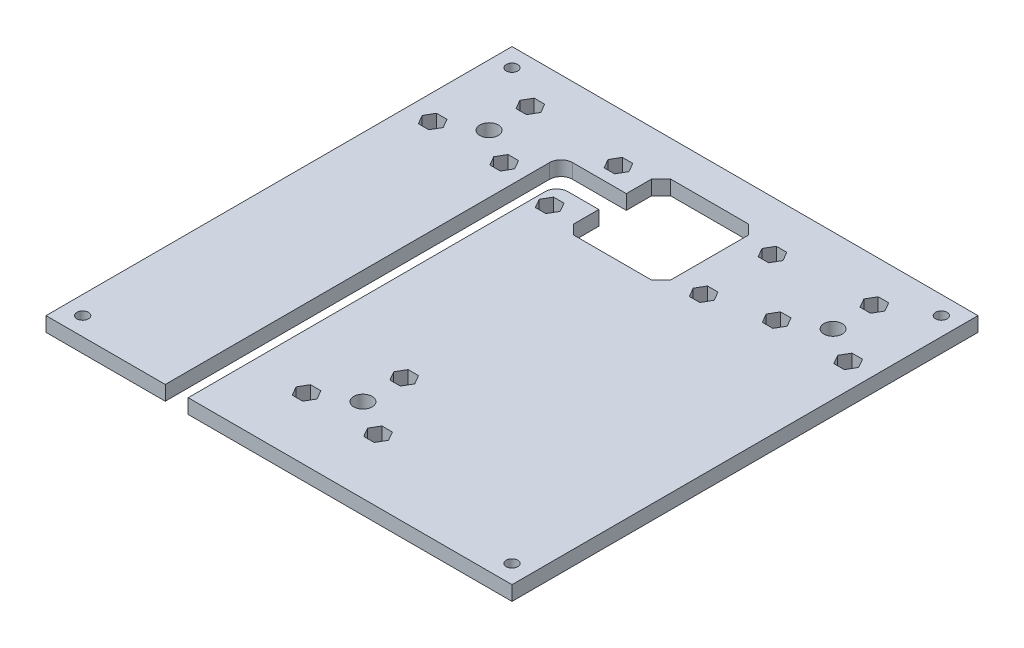
SolidWorks part; units mm, degrees
ref_plane "Plan de face" through (0, 0, 0) normal (0, 0, 1) x (1, 0, 0)
ref_plane "Plan de dessus" through (0, 0, 0) normal (0, 1, 0) x (1, 0, 0)
ref_plane "Plan de droite" through (0, 0, 0) normal (1, 0, 0) x (0, 0, -1)
sketch "Esquisse1" plane through (0, 0, 0) normal (0, 1, 0) x (1, 0, 0)
  line L1 (-101.6, -101.6) -> (101.6, -101.6)
  line L2 (-101.6, -101.6) -> (-101.6, 101.6)
  line L3 (-101.6, 101.6) -> (101.6, 101.6)
  line L4 (101.6, -101.6) -> (101.6, 101.6)
  line L5 (-101.6, -101.6) -> (101.6, 101.6) construction
  line L6 (-101.6, 101.6) -> (101.6, -101.6) construction
  point P0 (0, 0)
  dimension "D1" = 203.2
extrude "Boss.-Extru.1" add sketch "Esquisse1" along normal blind 6.35
sketch "Esquisse2" plane through (0, 6.35, 0) normal (0, 1, 0) x (1, 0, 0)
  circle A0 centre (-75, 65) radius 4
  circle A1 centre (75, 65) radius 4
  circle A2 centre (0, -65) radius 4
  dimension "D1" = 8
  dimension "D2" = 65
  dimension "D3" = 65
  dimension "D4" = 150
  dimension "D5" = 75
extrude "Enlèv. mat.-Extru.1" cut sketch "Esquisse2" against normal through all
sketch "Esquisse3" plane through (0, 6.35, 0) normal (0, 1, 0) x (1, 0, 0)
  line L0 (-17.05, 86.15) -> (-21.15, 82.05)
  line L1 (-21.15, 82.05) -> (-21.15, 47.95)
  line L2 (-21.15, 47.95) -> (-17.05, 43.85)
  line L3 (-17.05, 43.85) -> (17.05, 43.85)
  line L4 (17.05, 43.85) -> (21.15, 47.95)
  line L5 (21.15, 47.95) -> (21.15, 82.05)
  line L6 (21.15, 82.05) -> (17.05, 86.15)
  line L7 (17.05, 86.15) -> (-17.05, 86.15)
  line L9 (-75, 65) -> (75, 65) construction
  point P8 (0, 43.85)
  point P11 (0, 86.15)
  point P12 (-21.15, 65)
  point P13 (21.15, 65)
  dimension "D2" = 42.3
  dimension "D3" = 34.1
extrude "Enlèv. mat.-Extru.2" cut sketch "Esquisse3" against normal through all
sketch "Esquisse4" plane through (0, 6.35, 0) normal (0, 1, 0) x (1, 0, 0)
  line L0 (-101.6, -101.6) -> (101.6, -101.6) construction
  line L1 (-49.6, -101.6) -> (-39.6, -101.6)
  line L2 (-49.6, -101.6) -> (-49.6, 71)
  line L4 (-39.6, -101.6) -> (-39.6, 59)
  line L5 (-21.15, 82.05) -> (-21.15, 47.95) construction
  line L6 (-49.6, 71) -> (-21.15, 71)
  line L8 (-39.6, 59) -> (-21.15, 59)
  line L9 (-21.15, 71) -> (-21.15, 59)
  line L10 (-101.6, 101.6) -> (-101.6, -101.6) construction
  dimension "D1" = 10
  dimension "D2" = 52
  dimension "D3" = 12
  dimension "D4" = 11.05
extrude "Enlèv. mat.-Extru.3" cut sketch "Esquisse4" against normal through all
fillet "Congé1" radius 5 2 edges at (-49.6, 3.175, -71) (-39.6, 3.175, -59)
sketch "Esquisse5" plane through (0, 6.35, 0) normal (0, 1, 0) x (1, 0, 0)
  line L0 (-28.8524, 49.85) -> (-31.1387, 45.89)
  line L1 (-33.425, 49.85) -> (-33.425, 54.8456) construction
  line L2 (-31.1387, 45.89) -> (-35.7113, 45.89)
  line L3 (-35.7113, 45.89) -> (-37.9976, 49.85)
  line L4 (-37.9976, 49.85) -> (-35.7113, 53.81)
  line L5 (-35.7113, 53.81) -> (-31.1387, 53.81)
  line L6 (-31.1387, 53.81) -> (-28.8524, 49.85)
  line L7 (-33.425, 49.85) -> (-37.4356, 49.85) construction
  point P2 (-33.425, 53.81)
  dimension "D1" = 7.92
  dimension "D2" = 7.92
  dimension "D3" = 7.92
extrude "Enlèv. mat.-Extru.5" cut sketch "Esquisse5" against normal through all
sketch "Esquisse7" plane through (0, 6.35, 0) normal (0, 1, 0) x (1, 0, 0)
  line L0 (-31.1387, 75.89) -> (-35.7113, 75.89)
  line L1 (-35.7113, 75.89) -> (-37.9976, 79.85)
  line L2 (-37.9976, 79.85) -> (-35.7113, 83.81)
  line L3 (-35.7113, 83.81) -> (-31.1387, 83.81)
  line L4 (-31.1387, 83.81) -> (-28.8524, 79.85)
  line L6 (-28.8524, 79.85) -> (-31.1387, 75.89)
  line L8 (-33.425, 79.85) -> (-37.5841, 79.85) construction
  line L9 (-33.425, 79.85) -> (-33.425, 74.6708) construction
  point P8 (-33.425, 75.89)
  dimension "D1" = 7.92
  dimension "D2" = 7.92
  dimension "D3" = 7.92
extrude "Enlèv. mat.-Extru.6" cut sketch "Esquisse7" against normal through all
sketch "Esquisse8" plane through (0, 6.35, 0) normal (0, 1, 0) x (1, 0, 0)
  line L0 (36.0113, 45.89) -> (31.4387, 45.89)
  line L1 (31.4387, 45.89) -> (29.1524, 49.85)
  line L2 (29.1524, 49.85) -> (31.4387, 53.81)
  line L3 (31.4387, 53.81) -> (36.0113, 53.81)
  line L4 (36.0113, 53.81) -> (38.2976, 49.85)
  line L5 (38.2976, 49.85) -> (36.0113, 45.89)
  line L6 (33.725, 49.85) -> (36.8565, 49.85) construction
  line L7 (33.725, 49.85) -> (33.725, 61.6399) construction
  point P9 (33.725, 45.89)
  dimension "D1" = 7.92
  dimension "D2" = 7.92
  dimension "D3" = 7.92
extrude "Enlèv. mat.-Extru.7" cut sketch "Esquisse8" against normal through all
sketch "Esquisse9" plane through (0, 6.35, 0) normal (0, 1, 0) x (1, 0, 0)
  line L0 (36.0113, 75.89) -> (31.4387, 75.89)
  line L1 (31.4387, 75.89) -> (29.1524, 79.85)
  line L2 (29.1524, 79.85) -> (31.4387, 83.81)
  line L3 (31.4387, 83.81) -> (36.0113, 83.81)
  line L4 (36.0113, 83.81) -> (38.2976, 79.85)
  line L5 (38.2976, 79.85) -> (36.0113, 75.89)
  line L6 (33.725, 79.85) -> (33.725, 71.0093) construction
  line L7 (33.725, 71.0093) -> (33.725, 79.85) construction
  line L8 (33.725, 79.85) -> (36.6273, 79.85) construction
  point P11 (33.725, 83.81)
  dimension "D1" = 7.92
  dimension "D2" = 7.92
  dimension "D3" = 7.92
extrude "Enlèv. mat.-Extru.8" cut sketch "Esquisse9" against normal through all
sketch "Esquisse10" plane through (0, 6.35, 0) normal (0, 1, 0) x (1, 0, 0)
  line L0 (101.6, 101.6) -> (-101.6, 101.6) construction
  line L1 (20.1611, -74) -> (17.8748, -70.04)
  line L2 (17.8748, -70.04) -> (13.3022, -70.04)
  line L3 (13.3022, -70.04) -> (11.0158, -74)
  line L4 (11.0158, -74) -> (13.3022, -77.96)
  line L5 (13.3022, -77.96) -> (17.8748, -77.96)
  line L6 (17.8748, -77.96) -> (20.1611, -74)
  line L7 (-20.1611, -74) -> (-17.8748, -77.96)
  line L8 (-17.8748, -77.96) -> (-13.3022, -77.96)
  line L9 (-13.3022, -77.96) -> (-11.0158, -74)
  line L10 (-11.0158, -74) -> (-13.3022, -70.04)
  line L11 (-13.3022, -70.04) -> (-17.8748, -70.04)
  line L12 (-17.8748, -70.04) -> (-20.1611, -74)
  line L13 (-4.5726, -47) -> (-2.2863, -50.96)
  line L14 (-2.2863, -50.96) -> (2.2863, -50.96)
  line L15 (2.2863, -50.96) -> (4.5726, -47)
  line L16 (4.5726, -47) -> (2.2863, -43.04)
  line L17 (2.2863, -43.04) -> (-2.2863, -43.04)
  line L18 (-2.2863, -43.04) -> (-4.5726, -47)
  line L19 (-63.9842, 56) -> (-61.6978, 52.04)
  line L20 (-61.6978, 52.04) -> (-57.1252, 52.04)
  line L21 (-57.1252, 52.04) -> (-54.8389, 56)
  line L22 (-54.8389, 56) -> (-57.1252, 59.96)
  line L23 (-57.1252, 59.96) -> (-61.6978, 59.96)
  line L24 (-61.6978, 59.96) -> (-63.9842, 56)
  line L25 (-95.1611, 56) -> (-92.8748, 52.04)
  line L26 (-92.8748, 52.04) -> (-88.3022, 52.04)
  line L27 (-88.3022, 52.04) -> (-86.0158, 56)
  line L28 (-86.0158, 56) -> (-88.3022, 59.96)
  line L29 (-88.3022, 59.96) -> (-92.8748, 59.96)
  line L30 (-92.8748, 59.96) -> (-95.1611, 56)
  line L31 (-79.5726, 83) -> (-77.2863, 79.04)
  line L32 (-77.2863, 79.04) -> (-72.7137, 79.04)
  line L33 (-72.7137, 79.04) -> (-70.4274, 83)
  line L34 (-70.4274, 83) -> (-72.7137, 86.96)
  line L35 (-72.7137, 86.96) -> (-77.2863, 86.96)
  line L36 (-77.2863, 86.96) -> (-79.5726, 83)
  line L37 (54.8389, 56) -> (57.1252, 52.04)
  line L38 (57.1252, 52.04) -> (61.6978, 52.04)
  line L39 (61.6978, 52.04) -> (63.9842, 56)
  line L40 (63.9842, 56) -> (61.6978, 59.96)
  line L41 (61.6978, 59.96) -> (57.1252, 59.96)
  line L42 (57.1252, 59.96) -> (54.8389, 56)
  line L43 (95.1611, 56) -> (92.8748, 59.96)
  line L44 (92.8748, 59.96) -> (88.3022, 59.96)
  line L45 (88.3022, 59.96) -> (86.0158, 56)
  line L46 (86.0158, 56) -> (88.3022, 52.04)
  line L47 (88.3022, 52.04) -> (92.8748, 52.04)
  line L48 (92.8748, 52.04) -> (95.1611, 56)
  line L49 (70.4274, 83) -> (72.7137, 79.04)
  line L50 (72.7137, 79.04) -> (77.2863, 79.04)
  line L51 (77.2863, 79.04) -> (79.5726, 83)
  line L52 (79.5726, 83) -> (77.2863, 86.96)
  line L53 (77.2863, 86.96) -> (72.7137, 86.96)
  line L54 (72.7137, 86.96) -> (70.4274, 83)
  circle A0 centre (15.5885, -74) radius 3.96 construction
  circle A1 centre (-15.5885, -74) radius 3.96 construction
  circle A2 centre (0, -47) radius 3.96 construction
  circle A3 centre (-59.4115, 56) radius 3.96 construction
  circle A4 centre (-90.5885, 56) radius 3.96 construction
  circle A5 centre (-75, 83) radius 3.96 construction
  circle A6 centre (59.4115, 56) radius 3.96 construction
  circle A7 centre (90.5885, 56) radius 3.96 construction
  circle A8 centre (75, 83) radius 3.96 construction
  dimension "D1" = 7.92
extrude "Enlèv. mat.-Extru.9" cut sketch "Esquisse10" against normal through all
sketch "Esquisse11" plane through (0, 6.35, 0) normal (0, 1, 0) x (1, 0, 0)
  circle A0 centre (93.6, 93.6) radius 2.5
  circle A1 centre (-93.6, 93.6) radius 2.5
  circle A2 centre (-93.6, -93.6) radius 2.5
  circle A3 centre (93.6, -93.6) radius 2.5
extrude "Enlèv. mat.-Extru.10" cut sketch "Esquisse11" against normal through all
